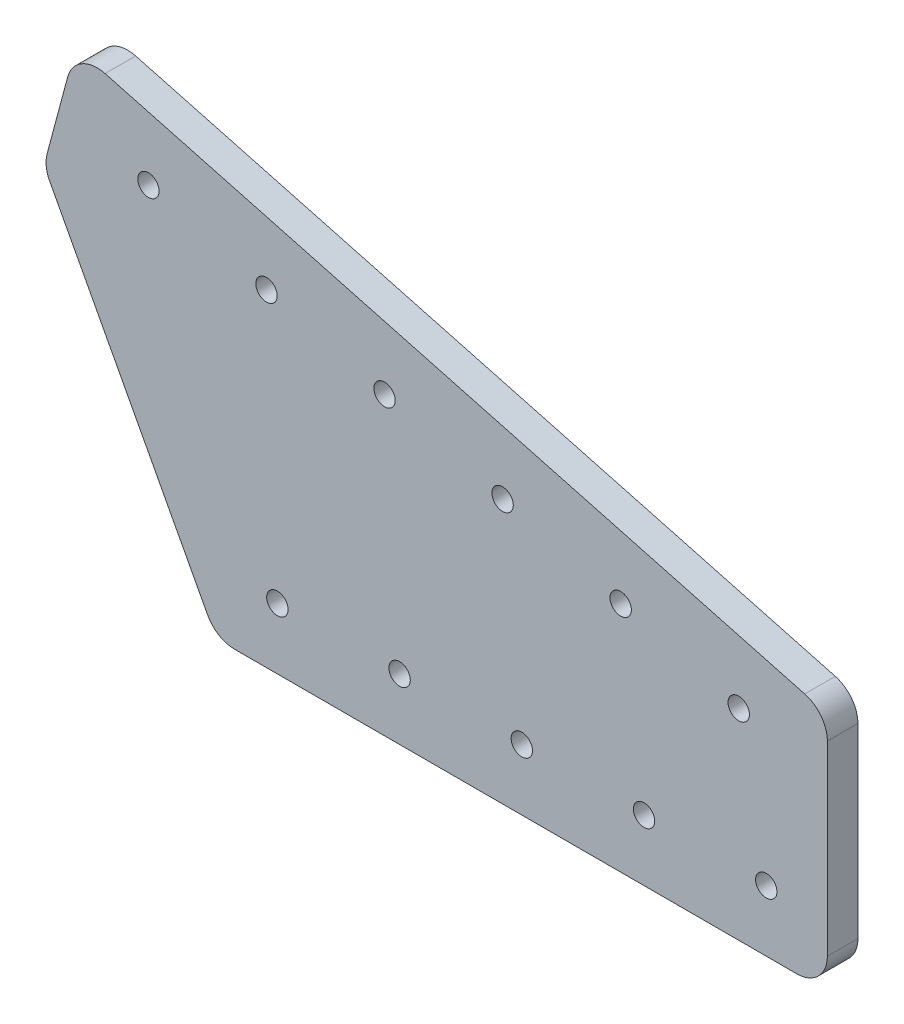
SolidWorks part; units mm, degrees
ref_plane "Plan de face" through (0, 0, 0) normal (0, 0, 1) x (1, 0, 0)
ref_plane "Plan de dessus" through (0, 0, 0) normal (0, 1, 0) x (1, 0, 0)
ref_plane "Plan de droite" through (0, 0, 0) normal (1, 0, 0) x (0, 0, -1)
sketch "Esquisse1" plane through (0, 0, 0) normal (0, 0, 1) x (1, 0, 0)
  line L0 (0, 0) -> (-56.3898, 105.9254)
  line L1 (-56.3898, 105.9254) -> (-46.037, 144.5625)
  line L2 (200, 78.637) -> (200, 0)
  line L3 (200, 0) -> (0, 0)
  line L4 (-46.037, 144.5625) -> (200, 78.637)
  line L5 (200, 78.637) -> (189.6472, 40) construction
  line L6 (189.6472, 40) -> (189.6472, 0) construction
  dimension "D1" = 15
  dimension "D2" = 200
  dimension "D3" = 120
  dimension "D4" = 40
  dimension "D5" = 40
  dimension "D6" = 90
  dimension "D7" = 40
extrude "Boss.-Extru.1" add sketch "Esquisse1" along normal blind 10
fillet "Congé1" radius 10 5 edges at (0, 0, 5) (200, 0, 5) (200, 78.637, 5) (-46.037, 144.5625, 5) (-56.3898, 105.9254, 5)
sketch "Esquisse2" plane through (0, 0, 10) normal (0, 0, 1) x (1, 0, 0)
  line L0 (-51.2134, 125.2439) -> (200, 57.9315) construction
  line L1 (-48.6252, 134.9032) -> (-55.3695, 109.7331) construction
  line L2 (192.5882, 80.623) -> (-36.3777, 141.9743) construction
  line L3 (200, 10) -> (200, 70.9638) construction
  line L4 (74.3933, 91.5877) -> (79.5697, 110.9062) construction
  line L5 (200, 20) -> (0, 20) construction
  line L6 (0, 20) -> (0, 0) construction
  line L7 (100, 20) -> (100, 2.1518) construction
  circle A0 centre (-22.1993, 117.4696) radius 3.5
  circle A1 centre (16.4378, 107.1169) radius 3.5
  circle A2 centre (55.0748, 96.7641) radius 3.5
  circle A3 centre (93.7118, 86.4113) radius 3.5
  circle A4 centre (132.3489, 76.0586) radius 3.5
  circle A5 centre (170.9859, 65.7058) radius 3.5
  circle A6 centre (20, 20) radius 3.5
  circle A7 centre (60, 20) radius 3.5
  circle A8 centre (100, 20) radius 3.5
  circle A9 centre (180, 20) radius 3.5
  circle A10 centre (140, 20) radius 3.5
  dimension "D2" = 40
  dimension "D3" = 40
  dimension "D4" = 7
  dimension "D5" = 20
  dimension "D7" = 40
  dimension "D8" = 40
  dimension "D1" = 20
  dimension "D6" = 20
extrude "Enlèv. mat.-Extru.1" cut sketch "Esquisse2" against normal through all both and the other way through all
